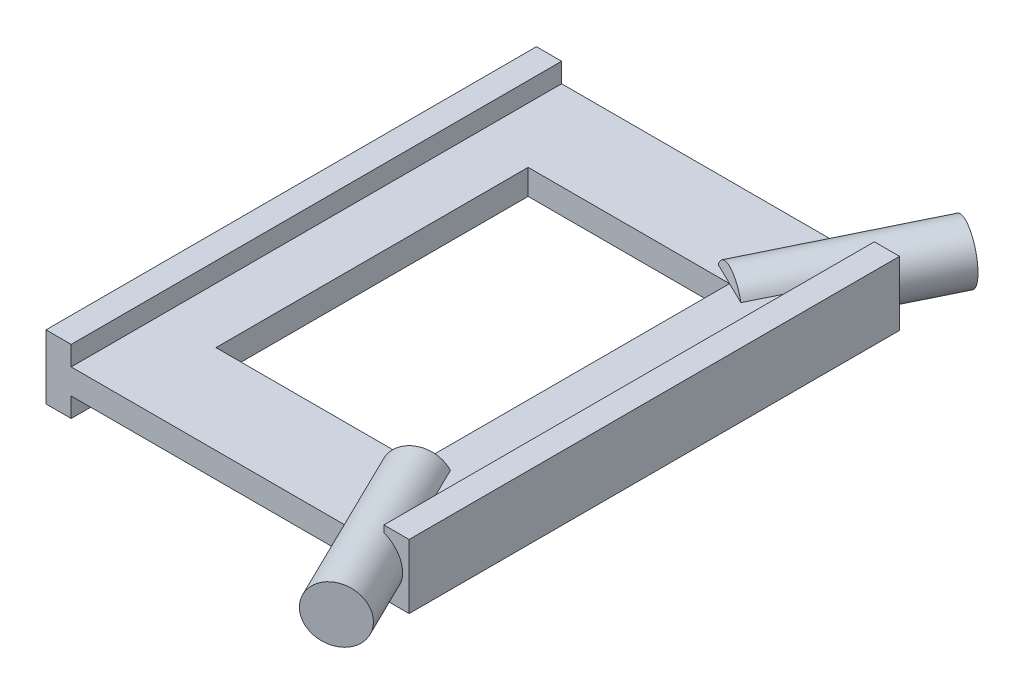
SolidWorks part; units mm, degrees
ref_plane "Front Plane" through (0, 0, 0) normal (0, 0, 1) x (1, 0, 0)
ref_plane "Top Plane" through (0, 0, 0) normal (0, 1, 0) x (1, 0, 0)
ref_plane "Right Plane" through (0, 0, 0) normal (1, 0, 0) x (0, 0, -1)
sketch "Sketch1" plane through (0, 0, 0) normal (0, 1, 0) x (1, 0, 0)
  line L1 (-36.055, -48.7) -> (36.055, -48.7)
  line L2 (-36.055, -48.7) -> (-36.055, 48.7)
  line L3 (-36.055, 48.7) -> (36.055, 48.7)
  line L4 (36.055, -48.7) -> (36.055, 48.7)
  line L5 (-36.055, -48.7) -> (36.055, 48.7) construction
  line L6 (-36.055, 48.7) -> (36.055, -48.7) construction
  point P0 (0, 0)
  dimension "D1" = 72.11
  dimension "D2" = 97.4
extrude "Boss-Extrude1" add sketch "Sketch1" along normal mid plane 5
sketch "Sketch2" plane through (0, 0, 0) normal (0, 1, 0) x (1, 0, 0)
  line L0 (-36.055, -48.7) -> (36.055, -48.7) construction
  line L1 (-36.055, 48.7) -> (-31.055, 48.7)
  line L2 (-36.055, 48.7) -> (-36.055, -48.7)
  line L3 (-36.055, -48.7) -> (-31.055, -48.7)
  line L4 (-31.055, 48.7) -> (-31.055, -48.7)
  line L6 (36.055, 48.7) -> (31.055, 48.7)
  line L7 (36.055, 48.7) -> (36.055, -48.7)
  line L8 (36.055, -48.7) -> (31.055, -48.7)
  line L9 (31.055, 48.7) -> (31.055, -48.7)
  dimension "D1" = 5
extrude "Boss-Extrude2" add sketch "Sketch2" along normal mid plane 12.75
sketch "Sketch3" plane through (0, 2.5, 0) normal (0, 1, 0) x (1, 0, 0)
  line L5 (-20, -31) -> (20, -31)
  line L6 (-20, -31) -> (-20, 31)
  line L7 (-20, 31) -> (20, 31)
  line L8 (20, -31) -> (20, 31)
  line L9 (-20, -31) -> (20, 31) construction
  line L10 (-20, 31) -> (20, -31) construction
  point P0 (0, 0)
  dimension "D1" = 40
  dimension "D2" = 62
extrude "Cut-Extrude1" cut sketch "Sketch3" against normal through all both and the other way through all
sketch "Sketch4" plane through (0, 0, 0) normal (0, 1, 0) x (1, 0, 0)
  line L0 (20, 31) -> (28.6492, 48.7) construction
  line L1 (31.055, 48.7) -> (-31.055, 48.7) construction
  line L2 (20, 31) -> (15.0584, 33.4147)
  line L3 (15.0584, 33.4147) -> (30.4249, 64.8611)
  line L4 (30.4249, 64.8611) -> (35.3664, 62.4464)
  line L5 (35.3664, 62.4464) -> (20, 31)
  dimension "D1" = 5.5
  dimension "D2" = 35
revolve "Revolve1" add sketch "Sketch4" angle 360 about L0
mirror "Mirror1" about plane through (0, 0, 0) normal (0, 0, 1) of "Revolve1"
